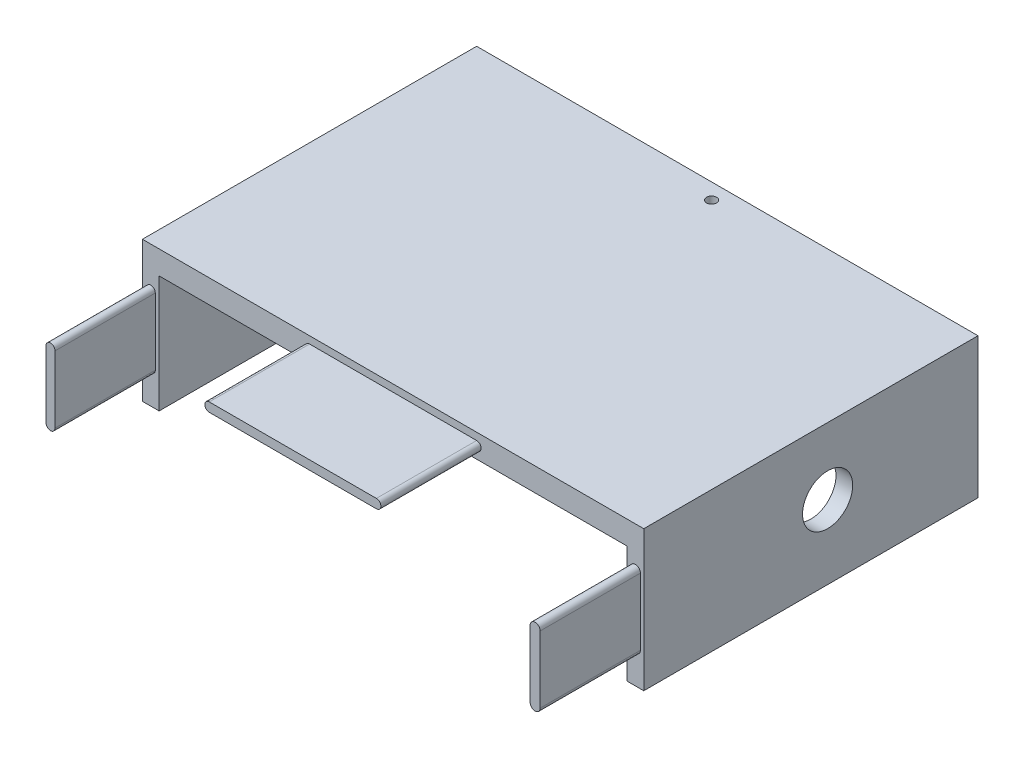
SolidWorks part; units mm, degrees
ref_plane "Front Plane" through (0, 0, 0) normal (0, 0, 1) x (1, 0, 0)
ref_plane "Top Plane" through (0, 0, 0) normal (0, 1, 0) x (1, 0, 0)
ref_plane "Right Plane" through (0, 0, 0) normal (1, 0, 0) x (0, 0, -1)
sketch "Sketch3" plane through (0, 0, 0) normal (0, 0, 1) x (1, 0, 0)
  line L0 (-106.5485, -30.2773) -> (-106.5485, 11.7227)
  line L1 (-106.5485, 11.7227) -> (43.4515, 11.7227)
  line L2 (43.4515, 11.7227) -> (43.4515, -30.2773)
  line L3 (43.4515, -30.2773) -> (38.4515, -30.2773)
  line L4 (38.4515, -30.2773) -> (38.4515, 4.7227)
  line L5 (38.4515, 4.7227) -> (-101.5485, 4.7227)
  line L6 (-101.5485, 4.7227) -> (-101.5485, -30.2773)
  line L7 (-101.5485, -30.2773) -> (-106.5485, -30.2773)
  dimension "D1" = 150
  dimension "D2" = 42
  dimension "D3" = 5
  dimension "D4" = 5
  dimension "D5" = 7
  dimension "D6" = 42
extrude "Boss-Extrude2" add sketch "Sketch3" along normal blind 100
sketch "Sketch4" plane through (0, 0, 100) normal (0, 0, 1) x (1, 0, 0)
  line L0 (-104.0485, -0.2773) -> (-104.0485, -20.2773) construction
  line L1 (-102.6985, -0.2773) -> (-102.6985, -20.2773)
  line L2 (-105.3985, -0.2773) -> (-105.3985, -20.2773)
  line L3 (-56.5485, 8.2227) -> (-6.5485, 8.2227) construction
  line L4 (-56.5485, 9.5727) -> (-6.5485, 9.5727)
  line L5 (-56.5485, 6.8727) -> (-6.5485, 6.8727)
  line L6 (40.9515, -0.2773) -> (40.9515, -20.2773) construction
  line L7 (42.4515, -0.2773) -> (42.4515, -20.2773)
  line L8 (39.4515, -0.2773) -> (39.4515, -20.2773)
  line L11 (-101.5485, 4.7227) -> (38.4515, 4.7227) construction
  line L12 (-106.5485, 11.7227) -> (-106.5485, -30.2773) construction
  line L13 (-101.5485, -30.2773) -> (-101.5485, 4.7227) construction
  line L14 (38.4515, 4.7227) -> (38.4515, -30.2773) construction
  arc A0 (-102.6985, -0.2773) -> (-105.3985, -0.2773) centre (-104.0485, -0.2773) ccw
  arc A1 (-105.3985, -20.2773) -> (-102.6985, -20.2773) centre (-104.0485, -20.2773) ccw
  arc A2 (-56.5485, 9.5727) -> (-56.5485, 6.8727) centre (-56.5485, 8.2227) ccw
  arc A3 (-6.5485, 6.8727) -> (-6.5485, 9.5727) centre (-6.5485, 8.2227) ccw
  arc A4 (42.4515, -0.2773) -> (39.4515, -0.2773) centre (40.9515, -0.2773) ccw
  arc A5 (39.4515, -20.2773) -> (42.4515, -20.2773) centre (40.9515, -20.2773) ccw
  point P2 (-104.0485, -10.2773)
  point P7 (-31.5485, 8.2227)
  point P14 (40.9515, -10.2773)
  point P23 (0, 0)
  point P31 (41.0389, -6.5388)
  dimension "D2" = 2.7
  dimension "D3" = 20
  dimension "D4" = 2.5
  dimension "D5" = 3
  dimension "D6" = 20
  dimension "D7" = 15
  dimension "D8" = 15
  dimension "D9" = 3.5
  dimension "D10" = 2.7
  dimension "D11" = 75
  dimension "D12" = 50
  dimension "D13" = 2.5
extrude "Boss-Extrude3" add sketch "Sketch4" along normal blind 30
sketch "Sketch10" plane through (43.4515, 0, 0) normal (1, 0, 0) x (0, 0, -1)
  line L0 (0, -30.2773) -> (0, 11.7227) construction
  line L1 (-100, 11.7227) -> (0, 11.7227) construction
  circle A0 centre (-45, -8.2773) radius 7.5
  dimension "D1" = 15
  dimension "D2" = 45
  dimension "D3" = 20
extrude "Cut-Extrude2" cut sketch "Sketch10" against normal blind 210
ref_plane "Plane1" through (0, 0, 25) normal (0, 0, -1) x (-1, 0, 0)
ref_plane "Plane2" through (-31.5485, 0, 0) normal (-1, 0, 0) x (0, 0, 1)
sketch "Sketch15" plane through (0, 11.7227, 0) normal (0, 1, 0) x (1, 0, 0)
  line L0 (-31.5485, 23.1) -> (-31.5485, -23.1) construction
  line L1 (43.4515, -100) -> (43.4515, 0) construction
  line L2 (-106.5485, -100) -> (-106.5485, 0) construction
  circle A0 centre (-31.5485, -4.7142) radius 1.5
  dimension "D1" = 3
  dimension "D2" = 75
  dimension "D3" = 75
extrude "Cut-Extrude3" cut sketch "Sketch15" against normal blind 10
sketch "Sketch16" plane through (0, 4.7227, 0) normal (0, -1, 0) x (1, 0, 0)
  line L0 (38.4515, 75) -> (14.4515, 75)
  line L1 (38.4515, 100) -> (38.4515, 0) construction
  line L2 (14.4515, 75) -> (14.4515, 63)
  line L3 (14.4515, 63) -> (38.4515, 63)
  line L4 (38.4515, 100) -> (38.4515, 0) construction
  line L5 (38.4515, 63) -> (38.4515, 75)
  line L6 (-101.5485, 0) -> (38.4515, 0) construction
  dimension "D1" = 24
  dimension "D2" = 12
  dimension "D3" = 63
extrude "Boss-Extrude5" add sketch "Sketch16" along normal blind 2
sketch "Sketch17" plane through (0, 2.7227, 0) normal (0, -1, 0) x (-1, 0, 0)
  line L0 (-17.4515, -63) -> (-17.4515, -75)
  line L1 (-14.4515, -63) -> (-38.4515, -63) construction
  line L2 (-38.4515, -75) -> (-14.4515, -75) construction
  line L3 (-17.4515, -75) -> (-14.4515, -75)
  line L4 (-14.4515, -75) -> (-14.4515, -63)
  line L5 (-14.4515, -63) -> (-17.4515, -63)
  dimension "D1" = 3
extrude "Boss-Extrude6" add sketch "Sketch17" along normal blind 25
sketch "Sketch19" plane through (14.4515, 0, 0) normal (-1, 0, 0) x (0, 0, 1)
  line L0 (75, -22.2773) -> (63, -22.2773) construction
  circle A0 centre (69.4851, 0.2227) radius 3.5
  circle A1 centre (69.4851, -17.7773) radius 3.5
  dimension "D1" = 7
  dimension "D2" = 7
  dimension "D4" = 4.5
  dimension "D3" = 18
extrude "Cut-Extrude4" cut sketch "Sketch19" against normal blind 1
sketch "Sketch20" plane through (15.4515, 0, 0) normal (-1, 0, 0) x (0, 0, 1)
  circle A0 centre (69.4851, 0.2227) radius 1.55
  circle A1 centre (69.4851, -17.7773) radius 1.55
  dimension "D1" = 3.1
  dimension "D2" = 3.1
extrude "Cut-Extrude5" cut sketch "Sketch20" against normal blind 3
mirror "Mirror6" about plane through (-31.5485, 0, 0) normal (-1, 0, 0) of "Cut-Extrude5", "Cut-Extrude4", "Boss-Extrude5", "Boss-Extrude6"
sketch "Sketch21" plane through (0, 4.7227, 0) normal (0, -1, 0) x (1, 0, 0)
  line L0 (-9.0485, 0) -> (-9.0485, 1.5)
  line L1 (-101.5485, 0) -> (38.4515, 0) construction
  line L2 (-9.0485, 1.5) -> (-54.0485, 1.5)
  line L3 (-54.0485, 1.5) -> (-54.0485, 0)
  line L4 (-54.0485, 0) -> (-9.0485, 0)
  dimension "D1" = 1.5
  dimension "D2" = 45
  dimension "D3" = 52.5
  dimension "D4" = 52.5
extrude "Boss-Extrude7" add sketch "Sketch21" along normal blind 35
sketch "Sketch23" plane through (0, 0, 0) normal (0, 0, -1) x (-1, 0, 0)
  line L1 (9.0485, -30.2773) -> (9.0485, 4.7227) construction
  line L2 (54.0485, -30.2773) -> (54.0485, 4.7227) construction
  line L3 (54.0485, -30.2773) -> (9.0485, -30.2773) construction
  circle A0 centre (44.5485, -16.2773) radius 8.25
  circle A1 centre (18.5485, -16.2773) radius 8.25
  dimension "D1" = 16.5
  dimension "D2" = 16.5
  dimension "D3" = 26
  dimension "D4" = 9.5
  dimension "D5" = 9.5
  dimension "D6" = 14
  dimension "D7" = 14
extrude "Cut-Extrude6" cut sketch "Sketch23" against normal blind 40
sketch "Sketch24" plane through (0, 0, 0) normal (0, 0, -1) x (-1, 0, 0)
  line L0 (26.5485, -26.3207) -> (36.5485, -26.3207) construction
  line L1 (26.5485, -23.0953) -> (36.5485, -23.0953)
  line L2 (26.5485, -29.5461) -> (36.5485, -29.5461)
  line L3 (9.0485, -30.2773) -> (9.0485, 4.7227) construction
  line L4 (54.0485, -30.2773) -> (54.0485, 4.7227) construction
  arc A0 (26.5485, -23.0953) -> (26.5485, -29.5461) centre (26.5485, -26.3207) ccw
  arc A1 (36.5485, -29.5461) -> (36.5485, -23.0953) centre (36.5485, -26.3207) ccw
  point P2 (31.5485, -26.3207)
  dimension "D1" = 10
  dimension "D2" = 22.5
  dimension "D3" = 22.5
extrude "Cut-Extrude7" cut sketch "Sketch24" against normal blind 40
